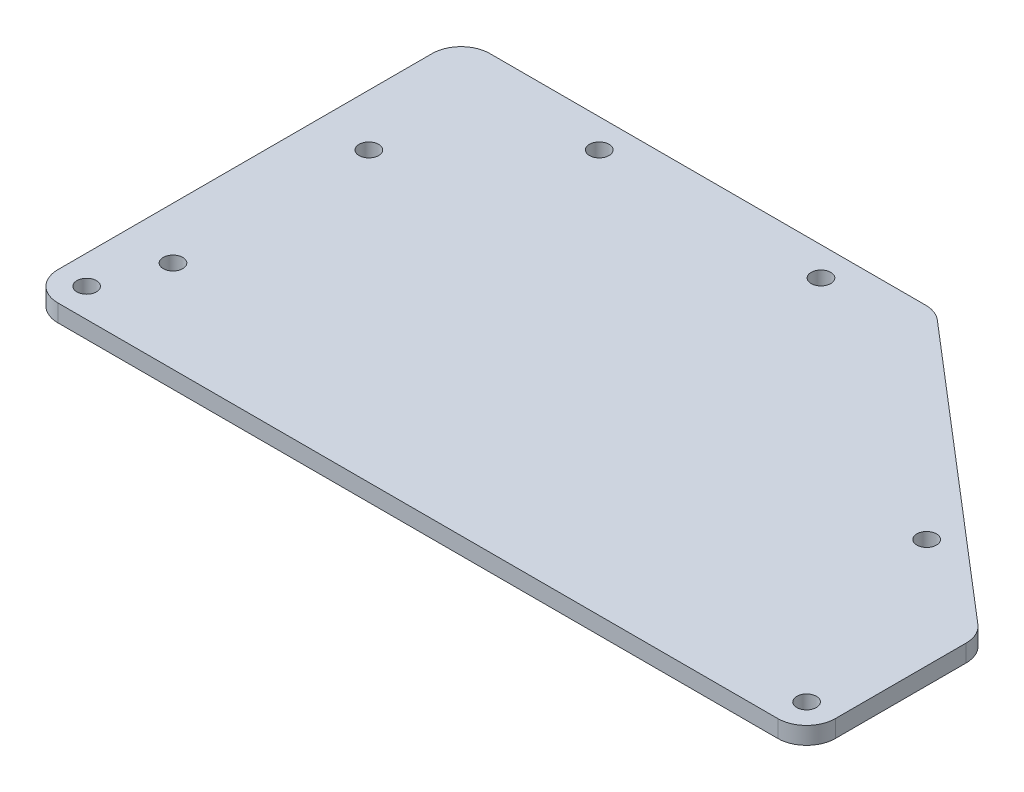
SolidWorks part; units mm, degrees
ref_plane "Front" through (0, 0, 0) normal (0, 0, 1) x (1, 0, 0)
ref_plane "Top" through (0, 0, 0) normal (0, 1, 0) x (1, 0, 0)
ref_plane "Right" through (0, 0, 0) normal (1, 0, 0) x (0, 0, -1)
sketch "Esquisse1" plane through (0, 0, 0) normal (0, 1, 0) x (1, 0, 0)
  line L0 (-67.5, 0) -> (67.5, 0)
  line L1 (0, 0) -> (67.5, 0) construction
  line L2 (0, 0) -> (0, 75) construction
  line L3 (0, 75) -> (67.5, 75) construction
  line L4 (67.5, 0) -> (67.5, 75) construction
  line L5 (67.5, 0) -> (67.5, 30)
  line L6 (67.5, 30) -> (15, 75)
  line L7 (15, 75) -> (-15, 75)
  line L9 (-67.5, 0) -> (-67.5, 30)
  line L10 (-67.5, 30) -> (-67.5, 75)
  line L11 (-67.5, 75) -> (-15, 75)
  dimension "D1" = 67.5
  dimension "D2" = 30
  dimension "D3" = 15
  dimension "D4" = 75
extrude "Boss.-Extru.1" add sketch "Esquisse1" along normal blind 3
fillet "Congé1" radius 5 5 edges at (-67.5, 1.5, 0) (15, 1.5, -75) (67.5, 1.5, -30) (67.5, 1.5, 0) (-67.5, 1.5, -75)
sketch "Esquisse2" plane through (0, 3, 0) normal (0, 1, 0) x (1, 0, 0)
  line L0 (-62.5, 0) -> (62.5, 0) construction
  line L1 (67.5, 5) -> (67.5, 27.7003) construction
  line L2 (13.1504, 75) -> (-62.5, 75) construction
  line L3 (-67.5, 70) -> (-67.5, 5) construction
  circle A0 centre (-62.5, 5) radius 1
  circle A1 centre (62.5, 5) radius 1
  circle A2 centre (0, 70) radius 1
  circle A3 centre (-58.5, 15.99) radius 1.5
  circle A4 centre (-58.5, 50) radius 1.5
  circle A5 centre (-38.5, 70) radius 1.5
  circle A6 centre (48.5, 39.85) radius 1.5
  dimension "D4" = 2
  dimension "D5" = 2
  dimension "D6" = 2
  dimension "D11" = 3
  dimension "D15" = 3
  dimension "D17" = 3
  dimension "D21" = 3
  dimension "D1" = 62.5
  dimension "D2" = 62.5
  dimension "D3" = 65
  dimension "D7" = 5
  dimension "D8" = 5
  dimension "D9" = 67.5
  dimension "D10" = 59.01
  dimension "D12" = 9
  dimension "D13" = 9
  dimension "D14" = 25
  dimension "D16" = 29
  dimension "D18" = 5
  dimension "D19" = 35.15
  dimension "D20" = 19
extrude "Enlèv. mat.-Extru.2" cut sketch "Esquisse2" against normal up to surface (3 mm away) up to face at (3.2296, 0, -36.244)
hole_wizard "Dégagement M31" positions "Esquisse3" profile "Esquisse4" hole size "M3" standard "ISO"
sketch "Esquisse3" plane through (0, 3, 0) normal (0, 1, 0) x (1, 0, 0)
  point P0 (-62.5, 5)
  point P3 (62.5, 5)
  point P6 (0, 70)
  point P9 (-58.5, 15.99)
  point P12 (-58.5, 50)
  point P15 (-38.5, 70)
  point P18 (48.5, 39.85)
sketch "Esquisse4" plane through (-62.5, 3, -5) normal (1, 0, 0) x (0, 0, 1)
  line L0 (0, 0) -> (0, 11.0215)
  line L1 (0, 11.0215) -> (1.7, 10)
  line L2 (1.7, 10) -> (1.7, 0)
  line L5 (1.7, 0) -> (0, 0)
  line L10 (0, 11.0215) -> (-1.7, 10) construction
  line L11 (0, -6.35) -> (0, 107.95) construction
  dimension "Diamètre du perçage" = 3.4
  dimension "Profondeur du perçage" = 10
  dimension "Angle de pointe" = 118
equation "\"D1@Esquisse1\"=135/2"
equation "\"D1@Esquisse2\"=125/2"
